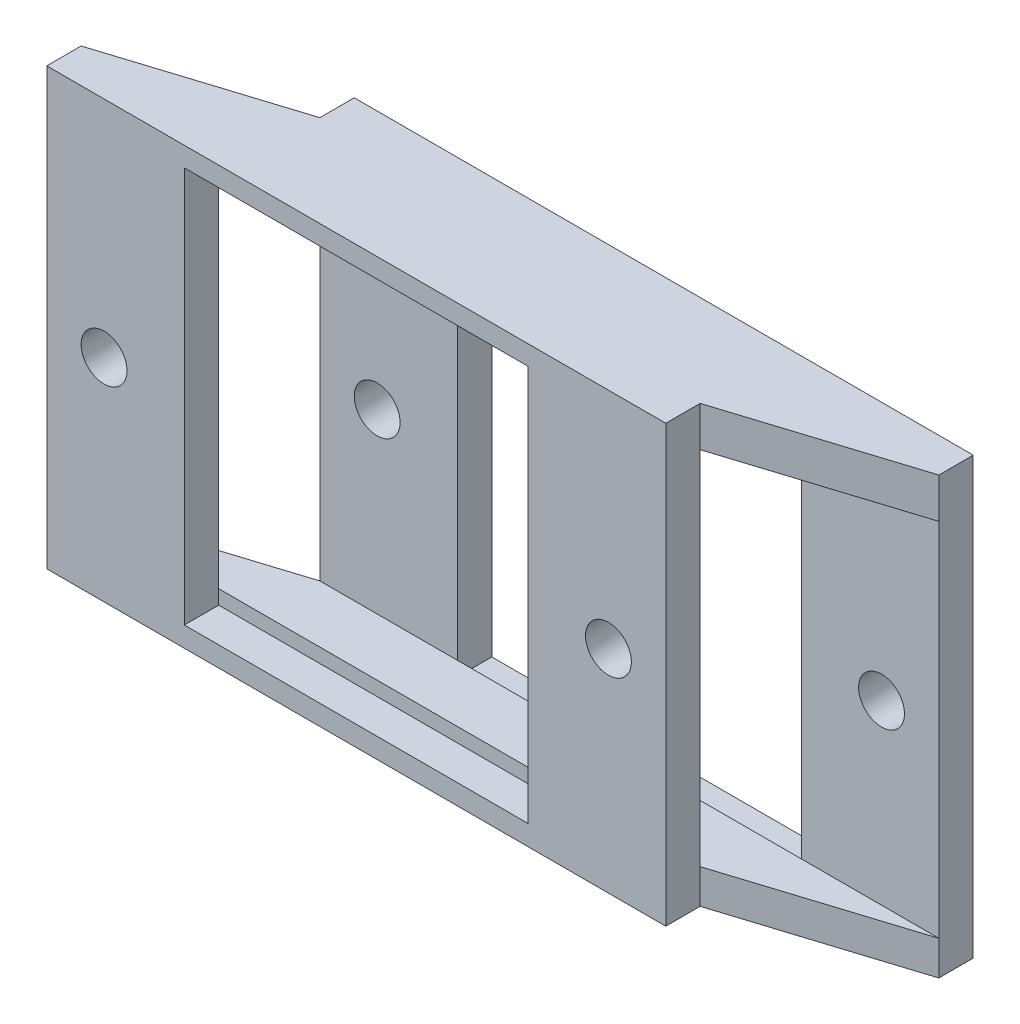
SolidWorks part; units mm, degrees
ref_plane "前视基准面" through (0, 0, 0) normal (0, 0, 1) x (1, 0, 0)
ref_plane "上视基准面" through (0, 0, 0) normal (0, 1, 0) x (1, 0, 0)
ref_plane "右视基准面" through (0, 0, 0) normal (1, 0, 0) x (0, 0, -1)
other "Configuration Table"
sketch "草图1" plane through (0, 0, 0) normal (0, 0, 1) x (1, 0, 0)
  line L1 (-35.445, 28.0661) -> (18.555, 28.0661)
  line L2 (-35.445, 28.0661) -> (-35.445, -9.9339)
  line L3 (-35.445, -9.9339) -> (18.555, -9.9339)
  line L4 (18.555, 28.0661) -> (18.555, -9.9339)
  dimension "D1" = 38
  dimension "D2" = 54
extrude "凸台-拉伸1" add sketch "草图1" along normal blind 3
sketch "草图3" plane through (0, 0, 0) normal (0, 0, -1) x (-1, 0, 0)
  line L0 (-18.555, -9.9339) -> (-18.555, 28.0661) construction
  line L1 (-6.555, 26.3627) -> (23.445, 26.3627)
  line L2 (-6.555, 26.3627) -> (-6.555, -8.1773)
  line L3 (-6.555, -8.1773) -> (23.445, -8.1773)
  line L4 (23.445, 26.3627) -> (23.445, -8.1773)
  line L9 (-18.555, 28.0661) -> (-18.555, 8.5261)
  line L10 (-18.555, 8.5261) -> (-13.555, 8.5261)
  line L11 (35.445, 28.0661) -> (35.445, 8.5261)
  line L12 (35.445, 28.0661) -> (35.445, -9.9339) construction
  line L13 (35.445, 8.5261) -> (30.445, 8.5261)
  circle A0 centre (-13.555, 8.5261) radius 2
  circle A1 centre (30.445, 8.5261) radius 2
  dimension "D1" = 34.54
  dimension "D2" = 30
  dimension "D3" = 12
extrude "切除-拉伸1" cut sketch "草图3" against normal blind 34.54 contours L2 L1 L4 L3 | A0 | A1
ref_plane "基准面1" through (0, 0, -5) normal (0, 0, -1) x (-1, 0, 0)
sketch "草图4" plane through (15.8246, 0, -5) normal (0, 0, -1) x (-1, 0, 0)
  line L1 (-18.555, 28.0661) -> (35.445, 28.0661)
  line L2 (-18.555, 28.0661) -> (-18.555, -9.9339)
  line L3 (-18.555, -9.9339) -> (35.445, -9.9339)
  line L4 (35.445, 28.0661) -> (35.445, -9.9339)
  line L5 (-6.555, 26.3627) -> (23.445, 26.3627)
  line L6 (-6.555, 26.3627) -> (-6.555, -8.1773)
  line L7 (-6.555, -8.1773) -> (23.445, -8.1773)
  line L8 (23.445, 26.3627) -> (23.445, -8.1773)
  circle A0 centre (-13.555, 8.5261) radius 2
  circle A1 centre (30.445, 8.5261) radius 2
  dimension "D3" = 34.54
  dimension "D1" = 38
  dimension "D2" = 54
  dimension "D4" = 30
extrude "凸台-拉伸2" add sketch "草图4" along normal blind 3 separate body
sketch "草图5" plane through (0, 28.0661, 0) normal (0, 1, 0) x (1, 0, 0)
  line L0 (-19.6204, 5) -> (-35.445, 0)
  line L1 (18.555, 0) -> (-35.445, 0) construction
  line L2 (-35.445, -3) -> (-35.445, 0) construction
  line L3 (-35.445, 0) -> (18.555, 0)
  line L4 (18.555, 0) -> (34.3796, 5)
  line L5 (34.3796, 8) -> (34.3796, 5) construction
  line L6 (-19.6204, 5) -> (34.3796, 5) construction
  line L7 (34.3796, 5) -> (-19.6204, 5)
extrude "凸台-拉伸3" add sketch "草图5" against normal blind 3.5
sketch "草图6" plane through (0, -9.9339, 0) normal (0, -1, 0) x (1, 0, 0)
  line L0 (-35.445, 0) -> (-19.6204, -5)
  line L1 (-19.6204, -5) -> (34.3796, -5)
  line L2 (34.3796, -5) -> (18.555, 0)
  line L3 (18.555, 0) -> (-35.445, 0)
extrude "凸台-拉伸4" add sketch "草图6" against normal blind 3
